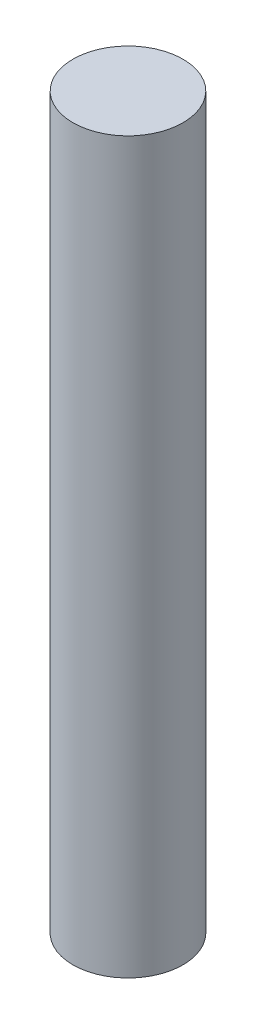
SolidWorks part; units mm, degrees
ref_plane "Front Plane" through (0, 0, 0) normal (0, 0, 1) x (1, 0, 0)
ref_plane "Top Plane" through (0, 0, 0) normal (0, 1, 0) x (1, 0, 0)
ref_plane "Right Plane" through (0, 0, 0) normal (1, 0, 0) x (0, 0, -1)
sketch "Sketch1" plane through (0, 0, 0) normal (0, 1, 0) x (1, 0, 0)
  circle A0 centre (7.8081, 19.8154) radius 2
extrude "Boss-Extrude2" add sketch "Sketch1" along normal blind 26.5
